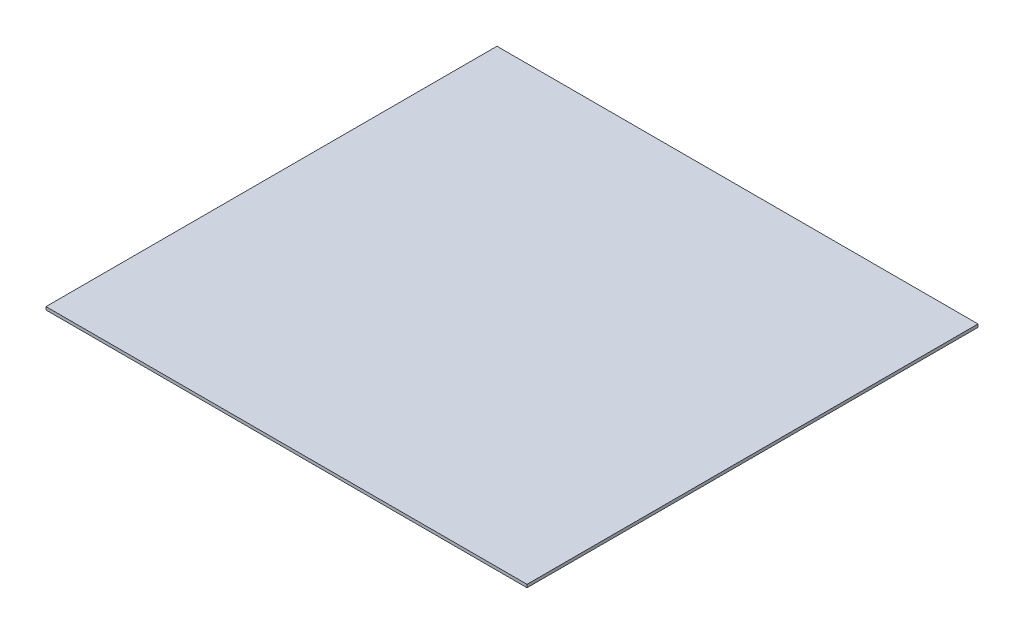
SolidWorks part; units mm, degrees
ref_plane "Front Plane" through (0, 0, 0) normal (0, 0, 1) x (1, 0, 0)
ref_plane "Top Plane" through (0, 0, 0) normal (0, 1, 0) x (1, 0, 0)
ref_plane "Right Plane" through (0, 0, 0) normal (1, 0, 0) x (0, 0, -1)
sketch "Sketch1" plane through (0, 0, 0) normal (0, 1, 0) x (1, 0, 0)
  line L1 (-406.4, -381) -> (406.4, -381)
  line L2 (-406.4, -381) -> (-406.4, 381)
  line L3 (-406.4, 381) -> (406.4, 381)
  line L4 (406.4, -381) -> (406.4, 381)
  line L5 (-406.4, -381) -> (406.4, 381) construction
  line L6 (-406.4, 381) -> (406.4, -381) construction
  point P0 (0, 0)
  dimension "D1" = 762
  dimension "D2" = 812.8
extrude "Boss-Extrude1" add sketch "Sketch1" along normal blind 5.08
